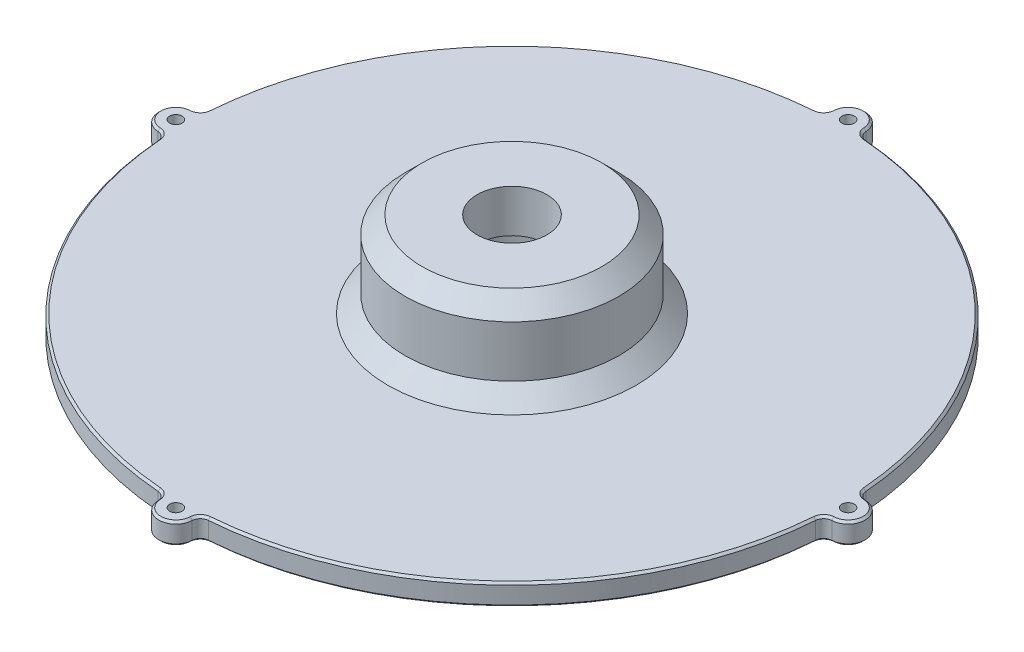
SolidWorks part; units mm, degrees
ref_plane "Płaszczyzna przednia" through (0, 0, 0) normal (0, 0, 1) x (1, 0, 0)
ref_plane "Płaszczyzna górna" through (0, 0, 0) normal (0, 1, 0) x (1, 0, 0)
ref_plane "Płaszczyzna prawa" through (0, 0, 0) normal (1, 0, 0) x (0, 0, -1)
sketch "Szkic2" plane through (0, 0, 0) normal (0, 0, 1) x (1, 0, 0)
  line L0 (15, 5) -> (15, 0)
  line L1 (15, 0) -> (77, 0)
  line L2 (77, 0) -> (77, 5)
  line L5 (77, 5) -> (15, 5)
  line L6 (0, 0) -> (0, 12.2819) construction
  line L7 (15, 5) -> (15, 15)
  line L8 (15, 15) -> (8.15, 15)
  line L9 (8.15, 15) -> (8.15, 25)
  line L10 (8.15, 25) -> (25, 25)
  line L11 (25, 25) -> (25, 5)
  dimension "D1" = 77
  dimension "D2" = 16.3
  dimension "D3" = 10
  dimension "D4" = 5
  dimension "D5" = 15
  dimension "D6" = 10
  dimension "D7" = 25
revolve "Obrót1" add sketch "Szkic2" angle 360 about L6
sketch "Szkic3" plane through (0, 5, 0) normal (0, 1, 0) x (1, 0, 0)
  line L0 (0, 76) -> (0, 78.5) construction
  line L1 (-4, 76) -> (-4, 78.5)
  line L2 (4, 76) -> (4, 78.5)
  line L3 (76, 0) -> (78.5, 0) construction
  line L4 (76, 4) -> (78.5, 4)
  line L5 (76, -4) -> (78.5, -4)
  line L6 (0, -76) -> (0, -78.5) construction
  line L7 (4, -76) -> (4, -78.5)
  line L8 (-4, -76) -> (-4, -78.5)
  line L9 (-76, 0) -> (-78.5, 0) construction
  line L10 (-76, -4) -> (-78.5, -4)
  line L11 (-76, 4) -> (-78.5, 4)
  arc A1 (-4, 76) -> (4, 76) centre (0, 76) ccw
  arc A2 (4, 78.5) -> (-4, 78.5) centre (0, 78.5) ccw
  circle A3 centre (0, 78.5) radius 1.45
  circle A4 centre (78.5, 0) radius 1.45
  arc A5 (76, 4) -> (76, -4) centre (76, 0) ccw
  arc A6 (78.5, -4) -> (78.5, 4) centre (78.5, 0) ccw
  circle A7 centre (0, -78.5) radius 1.45
  arc A8 (4, -76) -> (-4, -76) centre (0, -76) ccw
  arc A9 (-4, -78.5) -> (4, -78.5) centre (0, -78.5) ccw
  circle A10 centre (-78.5, 0) radius 1.45
  arc A11 (-76, -4) -> (-76, 4) centre (-76, 0) ccw
  arc A12 (-78.5, 4) -> (-78.5, -4) centre (-78.5, 0) ccw
  point P6 (0, 77.25)
  point P18 (77.25, 0)
  point P27 (0, -77.25)
  point P36 (-77.25, 0)
  point P43 (0, 0)
  dimension "D1" = 2.9
  dimension "D2" = 4
  dimension "D3" = 2.5
  dimension "D5" = 78.5
  dimension "D4" = 4
extrude "Dodanie-wyciągnięcie1" add sketch "Szkic3" against normal blind 5
sketch "Szkic4" plane through (0, 5, 0) normal (0, 1, 0) x (1, 0, 0)
  line L1 (-12.5, 12.5) -> (12.5, 12.5) construction
  line L2 (-12.5, 12.5) -> (-12.5, -12.5) construction
  line L3 (-12.5, -12.5) -> (12.5, -12.5) construction
  line L4 (12.5, 12.5) -> (12.5, -12.5) construction
  line L5 (-12.5, 12.5) -> (12.5, -12.5) construction
  line L6 (-12.5, -12.5) -> (12.5, 12.5) construction
  circle A0 centre (12.5, 12.5) radius 3.1
  circle A1 centre (12.5, -12.5) radius 3.1
  circle A2 centre (-12.5, -12.5) radius 3.1
  circle A3 centre (-12.5, 12.5) radius 3.1
  point P0 (0, 0)
  dimension "D2" = 6.2
  dimension "D1" = 25
chamfer "Sfazowanie1" distance 4 angle 45 2 edges at (0, 5, -25) (0, 25, -25)
fillet "Zaokrąglenie1" radius 2 8 edges at (76.896, 2.5, 4) (76.896, 2.5, -4) (4, 2.5, 76.896) (-4, 2.5, 76.896) (-76.896, 2.5, 4) (-76.896, 2.5, -4) (4, 2.5, -76.896) (-4, 2.5, -76.896)
chamfer "Sfazowanie2" distance 0.5 angle 45 37 edges at (0, 5, -82.5) (0, 0, -82.5) (77.3798, 5, 4.5582) (77.3798, 0, 4.5582) (77.3798, 5, -4.5582) (77.3798, 0, -4.5582) (4.5582, 5, 77.3798) (4.5582, 0, 77.3798) (-4.5582, 5, 77.3798) (-4.5582, 0, 77.3798) (-77.3798, 5, 4.5582) (-77.3798, 0, 4.5582) (-77.3798, 5, -4.5582) (-77.3798, 0, -4.5582) (4.5582, 5, -77.3798) (4.5582, 0, -77.3798) (-4.5582, 5, -77.3798) (-4.5582, 0, -77.3798) (-78.5, 0, 1.45) (0, 0, 79.95) (78.5, 0, 1.45) (0, 0, -77.05) (0, 0, -15) (54.4472, 5, 54.4472) (54.4472, 0, 54.4472) (82.5, 5, 0) (82.5, 0, 0) (54.4472, 5, -54.4472) (54.4472, 0, -54.4472) (0, 5, 82.5) (0, 0, 82.5) (-54.4472, 5, 54.4472) (-54.4472, 0, 54.4472) (-82.5, 5, 0) (-82.5, 0, 0) (-54.4472, 5, -54.4472) (-54.4472, 0, -54.4472)
